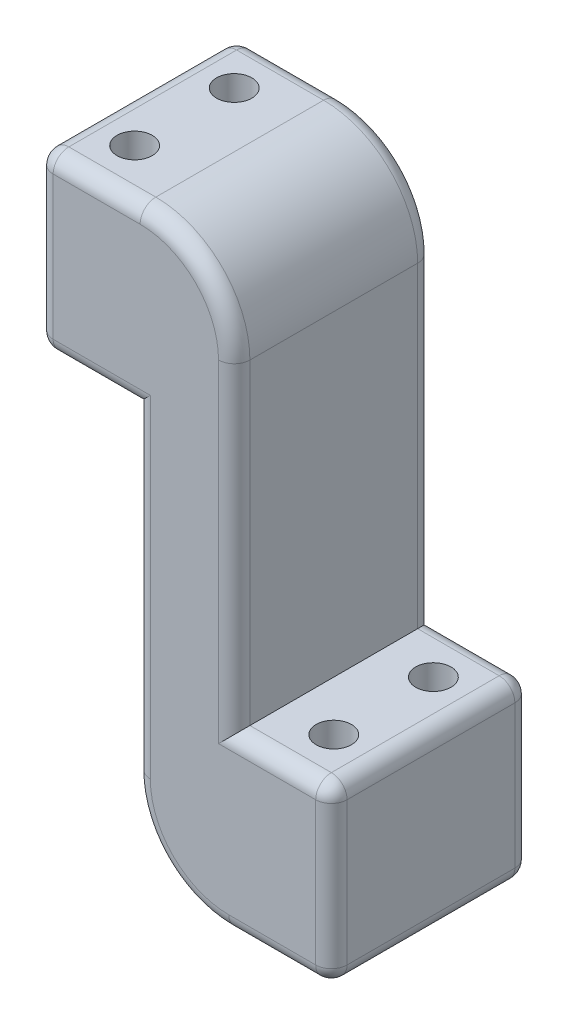
SolidWorks part; units mm, degrees
ref_plane "Front Plane" through (0, 0, 0) normal (0, 0, 1) x (1, 0, 0)
ref_plane "Top Plane" through (0, 0, 0) normal (0, 1, 0) x (1, 0, 0)
ref_plane "Right Plane" through (0, 0, 0) normal (1, 0, 0) x (0, 0, -1)
sketch "Sketch1" plane through (0, 0, 0) normal (0, 0, 1) x (1, 0, 0)
  line L0 (0, -23.8252) -> (-45.3315, -23.8252) construction
  line L1 (-2, 0) -> (-12.3952, 0)
  line L2 (0, -2) -> (0, -20.2504)
  line L3 (-2, -22.2504) -> (-12.3952, -22.2504)
  line L4 (-12.3952, 0) -> (-12.3952, -22.2504)
  line L5 (-25.0952, 30.1244) -> (-35.4904, 30.1244)
  line L6 (-25.0952, 30.1244) -> (-25.0952, 52.3748)
  line L7 (-25.0952, 52.3748) -> (-35.4904, 52.3748)
  line L8 (-37.4904, 32.1244) -> (-37.4904, 50.3748)
  line L9 (-25.0952, 52.3748) -> (-24.3952, 52.3748)
  line L10 (-12.3952, 40.3748) -> (-12.3952, 0)
  line L11 (-12.3952, -22.2504) -> (-13.0952, -22.2504)
  line L12 (-25.0952, -10.2504) -> (-25.0952, 30.1244)
  line L13 (-48.1495, 28.5496) -> (9.176, 28.5496) construction
  arc A0 (-13.0952, -22.2504) -> (-25.0952, -10.2504) centre (-13.0952, -10.2504) cw
  arc A1 (-12.3952, 40.3748) -> (-24.3952, 52.3748) centre (-24.3952, 40.3748) ccw
  arc A2 (0, -2) -> (-2, 0) centre (-2, -2) ccw
  arc A3 (0, -20.2504) -> (-2, -22.2504) centre (-2, -20.2504) cw
  arc A4 (-35.4904, 30.1244) -> (-37.4904, 32.1244) centre (-35.4904, 32.1244) cw
  arc A5 (-37.4904, 50.3748) -> (-35.4904, 52.3748) centre (-35.4904, 50.3748) cw
  point P19 (0, 0)
  point P22 (0, -22.2504)
  point P29 (-30.2928, 30.1244)
  dimension "D6" = 12
  dimension "D7" = 2
  dimension "D1" = 22.2504
  dimension "D2" = 12.3952
  dimension "D3" = 12.7
  dimension "D4" = 1.5748
  dimension "D5" = 1.5748
  dimension "D8" = 50.8
extrude "Boss-Extrude1" add sketch "Sketch1" along normal blind 25.4 contours L10 A1 L9 L6 L12 A0 L11 L4 | A5 L8 A4 L5 L6 L7 | A3 L2 A2 L1 L4 L3
sketch "Sketch2" plane through (0, 52.3748, 0) normal (0, 1, 0) x (1, 0, 0)
  line L0 (-35.4904, 0) -> (-24.3952, 0) construction
  line L1 (-37.4904, -25.4) -> (-37.4904, 0) construction
  line L2 (-35.4904, -25.4) -> (-24.3952, -25.4) construction
  line L3 (0, -25.4) -> (0, 0) construction
  circle A0 centre (-31.4452, -6.35) radius 2.25
  circle A1 centre (-31.4452, -19.05) radius 2.25
  circle A2 centre (-6.0452, -6.35) radius 2.25
  circle A3 centre (-6.0452, -19.05) radius 2.25
  point P14 (0, 0)
  point P15 (0, 0)
  point P16 (0, 0)
  point P17 (0, 0)
  point P20 (0, 0)
  dimension "D1" = 4.5
  dimension "D2" = 6.35
  dimension "D4" = 6.0452
  dimension "D5" = 6.35
  dimension "D6" = 6.0452
extrude "Cut-Extrude1" cut sketch "Sketch2" against normal through all
fillet "Fillet1" radius 2 28 edges at (-7.1976, 0, 0) (-0.5858, -0.5858, 0) (0, -11.1252, 0) (-0.5858, -21.6646, 0) (-7.5476, -22.2504, 0) (-21.5805, -18.7357, 0) (-7.1976, 0, 25.4) (-0.5858, -0.5858, 25.4) (0, -11.1252, 25.4) (-0.5858, -21.6646, 25.4) (-7.5476, -22.2504, 25.4) (-21.5805, -18.7357, 25.4) (-30.2928, 30.1244, 0) (-36.9046, 30.7102, 0) (-12.3952, 20.1874, 0) (-15.9099, 48.8601, 0) (-29.9428, 52.3748, 0) (-36.9046, 51.789, 0) (-12.3952, 20.1874, 25.4) (-30.2928, 30.1244, 25.4) (-36.9046, 30.7102, 25.4) (-37.4904, 41.2496, 0) (-37.4904, 41.2496, 25.4) (-36.9046, 51.789, 25.4) (-29.9428, 52.3748, 25.4) (-25.0952, 9.937, 0) (-25.0952, 9.937, 25.4) (-15.9099, 48.8601, 25.4)
